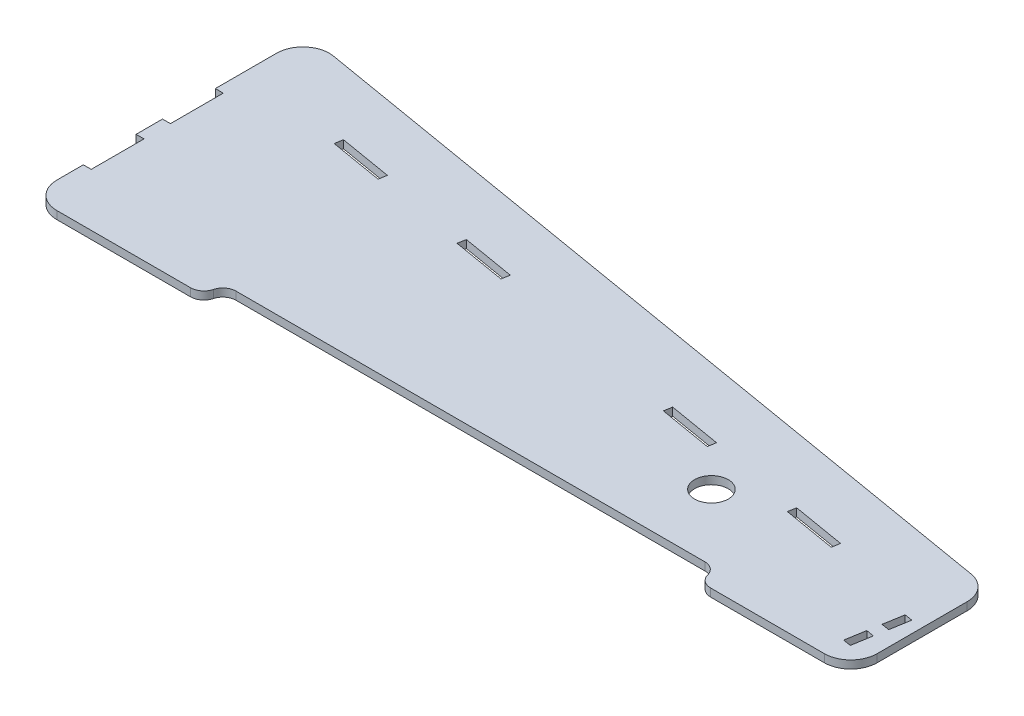
SolidWorks part; units mm, degrees
ref_plane "Front Plane" through (0, 0, 0) normal (0, 0, 1) x (1, 0, 0)
ref_plane "Top Plane" through (0, 0, 0) normal (0, 1, 0) x (1, 0, 0)
ref_plane "Right Plane" through (0, 0, 0) normal (1, 0, 0) x (0, 0, -1)
sketch "Sketch3" plane through (0, 0, 0) normal (0, 1, 0) x (1, 0, 0)
  line L0 (-257.2985, 138.5903) -> (-257.2985, -71.4097)
  line L1 (-257.2985, -71.4097) -> (363.8899, -71.4097)
  line L2 (363.8899, -71.4097) -> (363.8899, 33.5903)
  line L3 (363.8899, 33.5903) -> (-257.2985, 138.5903)
  dimension "D1" = 630
  dimension "D2" = 210
  dimension "D3" = 105
extrude "Boss-Extrude1" add sketch "Sketch3" along normal blind 6
sketch "Sketch4" plane through (0, 6, 0) normal (0, 1, 0) x (1, 0, 0)
  line L0 (-135.2354, 76.815) -> (-175.2354, 83.5763)
  line L1 (-37.5411, 101.4445) -> (-44.3023, 61.4445) construction
  line L2 (363.8899, 33.5903) -> (-257.2985, 138.5903) construction
  line L3 (-44.3023, 61.4445) -> (-257.2985, 97.4475) construction
  line L4 (-44.3023, 61.4445) -> (379.0145, -10.1091) construction
  line L9 (-135.2354, 76.815) -> (-136.2513, 70.805)
  line L10 (-175.2354, 83.5763) -> (-176.2513, 77.5663)
  line L11 (-136.2513, 70.805) -> (-176.2513, 77.5663)
  line L12 (-63.2564, 64.6484) -> (-64.2723, 58.6384)
  line L13 (-63.2564, 64.6484) -> (-23.2564, 57.8871)
  line L14 (-64.2723, 58.6384) -> (-24.2723, 51.8771)
  line L15 (-23.2564, 57.8871) -> (-24.2723, 51.8771)
  line L16 (124.7436, 32.8706) -> (164.7436, 26.1093)
  line L17 (124.7436, 32.8706) -> (123.7277, 26.8606)
  line L18 (164.7436, 26.1093) -> (163.7277, 20.0993)
  line L19 (123.7277, 26.8606) -> (163.7277, 20.0993)
  line L20 (237.7436, 13.7701) -> (277.7436, 7.0088)
  line L21 (237.7436, 13.7701) -> (236.7277, 7.7601)
  line L22 (277.7436, 7.0088) -> (276.7277, 0.9988)
  line L23 (236.7277, 7.7601) -> (276.7277, 0.9988)
  line L24 (-257.2985, 138.5903) -> (-257.2985, -71.4097) construction
  line L27 (350.7436, -5.3304) -> (338.9587, -75.0507) construction
  line L28 (349.0532, -15.3304) -> (346.5178, -30.3304)
  line L33 (349.0532, -15.3304) -> (355.0532, -16.3446)
  line L34 (346.5178, -30.3304) -> (352.5178, -31.3446)
  line L35 (355.0532, -16.3446) -> (352.5178, -31.3446)
  line L36 (344.8511, -40.1905) -> (342.3157, -55.1905)
  line L37 (344.8511, -40.1905) -> (350.8511, -41.2047)
  line L38 (342.3157, -55.1905) -> (348.3157, -56.2047)
  line L39 (350.8511, -41.2047) -> (348.3157, -56.2047)
  line L40 (348.3157, -56.2047) -> (345.7455, -71.4097) construction
  line L42 (-257.2985, -71.4097) -> (363.8899, -71.4097) construction
  line L43 (345.7455, -71.4097) -> (339.7455, -70.3955) construction
  line L44 (-248.2354, 95.9155) -> (-249.2513, 89.9055) construction
  line L45 (-249.2513, 89.9055) -> (337.3983, -9.2564) construction
  line L46 (337.3983, -9.2564) -> (338.4142, -3.2464) construction
  dimension "D1" = 90
  dimension "D2" = 40
  dimension "D3" = 40
  dimension "D4" = 73
  dimension "D5" = 40
  dimension "D6" = 40
  dimension "D7" = 40
  dimension "D8" = 73
  dimension "D9" = 148
  dimension "D10" = 6.01
  dimension "D11" = 6.01
  dimension "D12" = 6.01
  dimension "D13" = 6.01
  dimension "D14" = 83.2272
  dimension "D15" = 73
  dimension "D16" = 15
  dimension "D17" = 15
  dimension "D18" = 10
  dimension "D19" = 10
  dimension "D20" = 6
  dimension "D21" = 6
  dimension "D22" = 90
  dimension "D23" = 73
  dimension "D24" = 6.01
  dimension "D25" = 586.6496
extrude "Cut-Extrude1" cut sketch "Sketch4" against normal blind 6
sketch "Sketch6" plane through (0, 6, 0) normal (0, 1, 0) x (1, 0, 0)
  line L0 (-257.2985, -71.4097) -> (363.8899, -71.4097) construction
  line L1 (-126.6071, -71.4097) -> (248.3929, -71.4097)
  line L2 (-126.6071, -71.4097) -> (-126.6071, -56.4097)
  line L3 (-126.6071, -56.4097) -> (248.3929, -56.4097)
  line L4 (248.3929, -71.4097) -> (248.3929, -56.4097)
  dimension "D1" = 375
  dimension "D2" = 15
extrude "Cut-Extrude2" cut sketch "Sketch6" against normal blind 6
fillet "Fillet1" radius 10 1 edges at (-126.6071, 3, 56.4097)
fillet "Fillet2" radius 10 1 edges at (248.3929, 3, 56.4097)
fillet "Fillet4" radius 20 4 edges at (363.8899, 3, 71.4097) (363.8899, 3, -33.5903) (-257.2985, 3, -138.5903) (-257.2985, 3, 71.4097)
fillet "Fillet5" radius 10 2 edges at (248.3929, 3, 71.4097) (-126.6071, 3, 71.4097)
sketch "Sketch7" plane through (0, 6, 0) normal (0, 1, 0) x (1, 0, 0)
  line L0 (238.3929, -56.4097) -> (-116.6071, -56.4097) construction
  line L2 (363.8899, -51.4097) -> (363.8899, 16.6872) construction
  circle A0 centre (193.3722, -6.4097) radius 12.75
  dimension "D1" = 25.5
  dimension "D2" = 50
  dimension "D4" = 170.5176
extrude "Cut-Extrude3" cut sketch "Sketch7" against normal blind 10
sketch "Sketch9" plane through (0, 6, 0) normal (0, 1, 0) x (1, 0, 0)
  line L0 (-241.053, 177.5872) -> (-241.053, -92.5463) construction
  line L1 (-257.2985, 114.926) -> (-257.2985, -51.4097) construction
  line L2 (-257.2985, 68.5903) -> (-251.2985, 68.5903)
  line L3 (-257.2985, 68.5903) -> (-257.2985, 28.5903)
  line L4 (-257.2985, 28.5903) -> (-251.2985, 28.5903)
  line L5 (-251.2985, 68.5903) -> (-251.2985, 28.5903)
  line L6 (-237.2985, -71.4097) -> (-135.972, -71.4097) construction
  line L7 (-257.2985, 8.5903) -> (-251.2985, 8.5903)
  line L8 (-257.2985, 8.5903) -> (-257.2985, -31.4097)
  line L9 (-257.2985, -31.4097) -> (-251.2985, -31.4097)
  line L10 (-251.2985, 8.5903) -> (-251.2985, -31.4097)
  line L11 (347.2232, 36.4075) -> (-233.9652, 134.6463) construction
  dimension "D1" = 6
  dimension "D2" = 40
  dimension "D3" = 6
  dimension "D4" = 40
  dimension "D5" = 20
  dimension "D6" = 40
  dimension "D7" = 170.406
  dimension "D8" = 9.594
extrude "Cut-Extrude4" cut sketch "Sketch9" against normal blind 10
